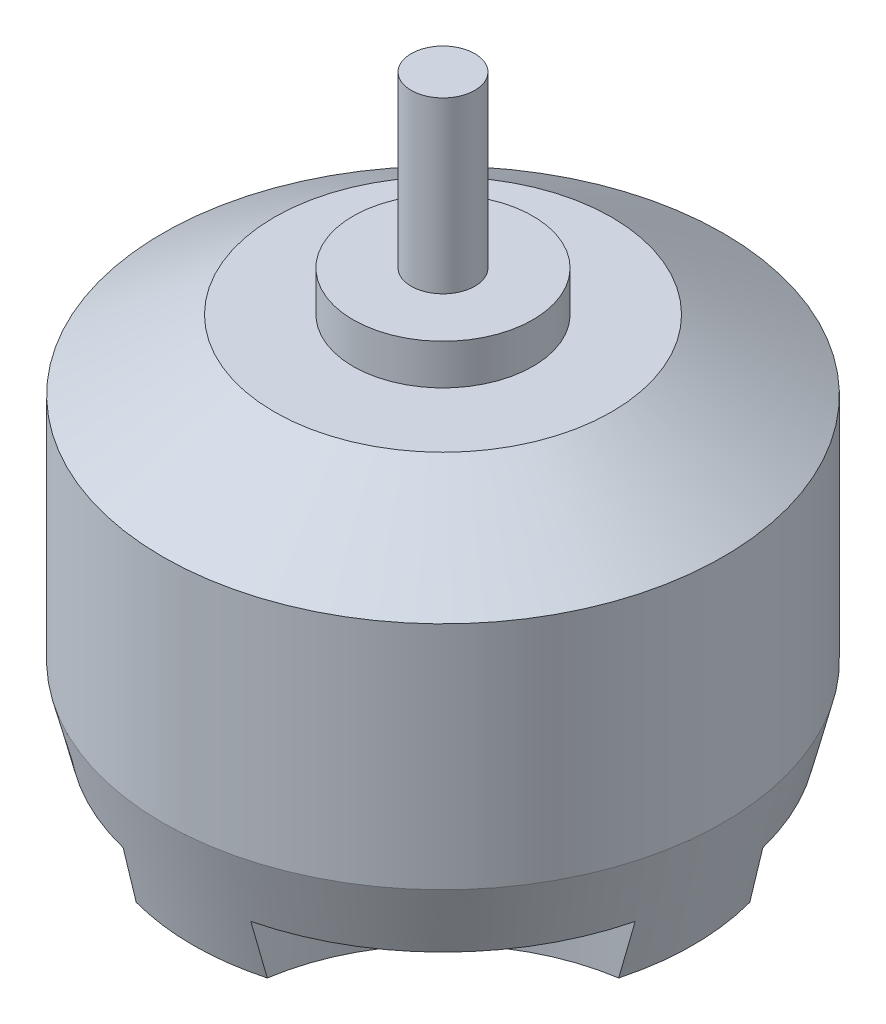
SolidWorks part; units mm, degrees
ref_plane "Front Plane" through (0, 0, 0) normal (0, 0, 1) x (1, 0, 0)
ref_plane "Top Plane" through (0, 0, 0) normal (0, 1, 0) x (1, 0, 0)
ref_plane "Right Plane" through (0, 0, 0) normal (1, 0, 0) x (0, 0, -1)
sketch "Sketch1" plane through (0, 0, 0) normal (0, 1, 0) x (1, 0, 0)
  circle A0 centre (0, 0) radius 13.875
  dimension "D1" = 27.75
extrude "Extrude1" add sketch "Sketch1" along normal blind 20.85
sketch "Sketch2" plane through (0, 0, 0) normal (0, 0, 1) x (1, 0, 0)
  line L0 (0, 20.85) -> (8.35, 20.85) construction
  line L1 (13.875, 20.85) -> (-13.875, 20.85) construction
  line L2 (8.35, 20.85) -> (13.875, 17.4)
  line L4 (13.875, 0) -> (13.875, 20.85) construction
  line L5 (13.875, 17.4) -> (13.875, 20.85)
  line L6 (13.875, 20.85) -> (8.35, 20.85)
  dimension "D1" = 8.35
  dimension "D2" = 3.45
ref_axis "Axis1" through (0, 20.85, 0) along (0, -1, 0)
revolve "Cut-Revolve1" cut sketch "Sketch2" angle 360 about axis through (0, 20.85, 0) along (0, -1, 0)
sketch "Sketch3" plane through (0, 20.85, 0) normal (0, 1, 0) x (1, 0, 0)
  circle A0 centre (0, 0) radius 4.45
  dimension "D1" = 8.9
extrude "Extrude2" add sketch "Sketch3" along normal blind 2
sketch "Sketch4" plane through (0, 0, 0) normal (0, -1, 0) x (1, 0, 0)
  line L0 (13.5185, 3.125) -> (13.5185, -3.125) construction
  line L1 (13.875, 0) -> (17.4379, 0) construction
  line L2 (3.125, -13.5185) -> (-3.125, -13.5185) construction
  line L3 (-13.5185, -3.125) -> (-13.5185, 3.125) construction
  line L4 (-3.125, 13.5185) -> (3.125, 13.5185) construction
  circle A0 centre (0, 0) radius 13.875 construction
  arc A1 (-13.5185, 3.125) -> (-3.125, 13.5185) centre (-13.5185, 13.5185) ccw
  arc A2 (3.125, 13.5185) -> (13.5185, 3.125) centre (13.5185, 13.5185) ccw
  arc A3 (13.5185, -3.125) -> (3.125, -13.5185) centre (13.5185, -13.5185) ccw
  arc A4 (-3.125, -13.5185) -> (-13.5185, -3.125) centre (-13.5185, -13.5185) ccw
  arc A5 (-13.5185, 3.125) -> (-3.125, 13.5185) centre (0, 0) cw
  arc A6 (3.125, 13.5185) -> (13.5185, 3.125) centre (0, 0) cw
  arc A7 (3.125, -13.5185) -> (13.5185, -3.125) centre (0, 0) ccw
  arc A8 (-13.5185, -3.125) -> (-3.125, -13.5185) centre (0, 0) ccw
  dimension "D1" = 6.25
extrude "Extrude3" cut sketch "Sketch4" against normal blind 2.75
sketch "Sketch5" plane through (0, 0, 0) normal (1, 0, 0) x (0, 0, -1)
  line L0 (-13.875, 0) -> (-12.375, 0)
  line L1 (-13.5185, 0) -> (-3.125, 0) construction
  line L2 (-12.375, 0) -> (-13.875, 6)
  line L3 (-13.875, 17.4) -> (-13.875, 0) construction
  line L4 (-13.875, 6) -> (-13.875, 0)
  dimension "D1" = 6
  dimension "D2" = 1.5
revolve "Cut-Revolve2" cut sketch "Sketch5" angle 360 about axis through (0, 20.85, 0) along (0, -1, 0)
sketch "Sketch6" plane through (0, 22.85, 0) normal (0, 1, 0) x (-1, 0, 0)
  circle A0 centre (0, 0) radius 1.575
  dimension "D1" = 3.15
extrude "Extrude4" add sketch "Sketch6" along normal blind 8.4
sketch "Sketch7" plane through (0, 0, 0) normal (0, -1, 0) x (1, 0, 0)
  circle A0 centre (0, 0) radius 1.575
extrude "Extrude5" add sketch "Sketch7" along normal blind 1.4
sketch "Sketch8" plane through (0, 0, 0) normal (0, -1, 0) x (1, 0, 0)
  line L0 (-6.75, 0) -> (-6.75, -1) construction
  line L1 (6.75, 0) -> (6.75, -1) construction
  line L2 (-9.15, 0) -> (-12.375, 0) construction
  line L3 (9.15, 0) -> (12.375, 0) construction
  line L4 (0, 8.25) -> (-1, 8.25) construction
  line L5 (0, -8.25) -> (-1, -8.25) construction
  line L6 (0, -10.65) -> (0, -12.375) construction
  line L7 (0, 10.65) -> (0, 12.375) construction
  circle A0 centre (-7.95, 0) radius 1.2
  circle A1 centre (7.95, 0) radius 1.2
  arc A2 (-11.9419, 3.2453) -> (-11.9419, -3.2453) centre (0, 0) ccw construction
  arc A3 (11.9419, -3.2453) -> (11.9419, 3.2453) centre (0, 0) ccw construction
  circle A4 centre (0, 9.45) radius 1.2
  circle A5 centre (0, -9.45) radius 1.2
  arc A7 (3.2453, 11.9419) -> (-3.2453, 11.9419) centre (0, 0) ccw construction
  arc A8 (-3.2453, -11.9419) -> (3.2453, -11.9419) centre (0, 0) ccw construction
  dimension "D2" = 2.4
  dimension "D3" = 2.4
  dimension "D4" = 2.4
  dimension "D5" = 2.4
  dimension "D1" = 13.5
  dimension "D6" = 16.5
extrude "Extrude7" cut sketch "Sketch8" against normal blind 3
